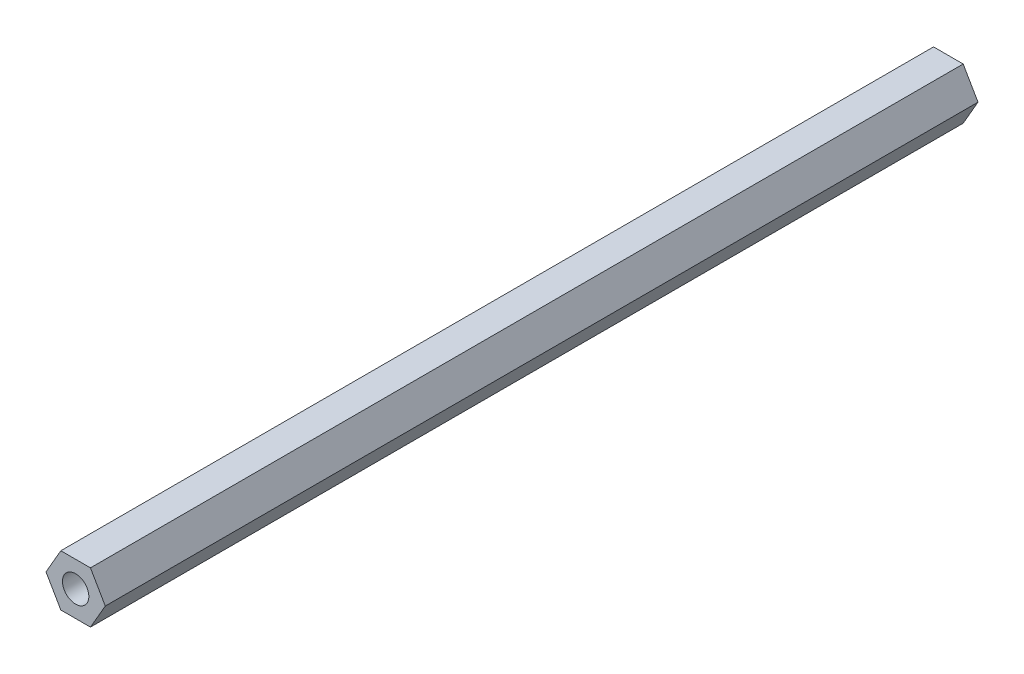
SolidWorks part; units mm, degrees
ref_plane "Front Plane" through (0, 0, 0) normal (0, 0, 1) x (1, 0, 0)
ref_plane "Top Plane" through (0, 0, 0) normal (0, 1, 0) x (1, 0, 0)
ref_plane "Right Plane" through (0, 0, 0) normal (1, 0, 0) x (0, 0, -1)
sketch "Sketch1" plane through (0, 0, 0) normal (0, 0, 1) x (1, 0, 0)
  line L1 (-7.3323, 0) -> (-3.6662, -6.35)
  line L2 (-3.6662, -6.35) -> (3.6662, -6.35)
  line L3 (3.6662, -6.35) -> (7.3323, 0)
  line L4 (7.3323, 0) -> (3.6662, 6.35)
  line L5 (3.6662, 6.35) -> (-3.6662, 6.35)
  line L6 (-3.6662, 6.35) -> (-7.3323, 0)
  circle A0 centre (0, 0) radius 6.35 construction
  circle A1 centre (0, 0) radius 3.2639
  dimension "D1" = 12.7
  dimension "D2" = 6.5278
extrude "Boss-Extrude1" add sketch "Sketch1" along normal blind 215.9
